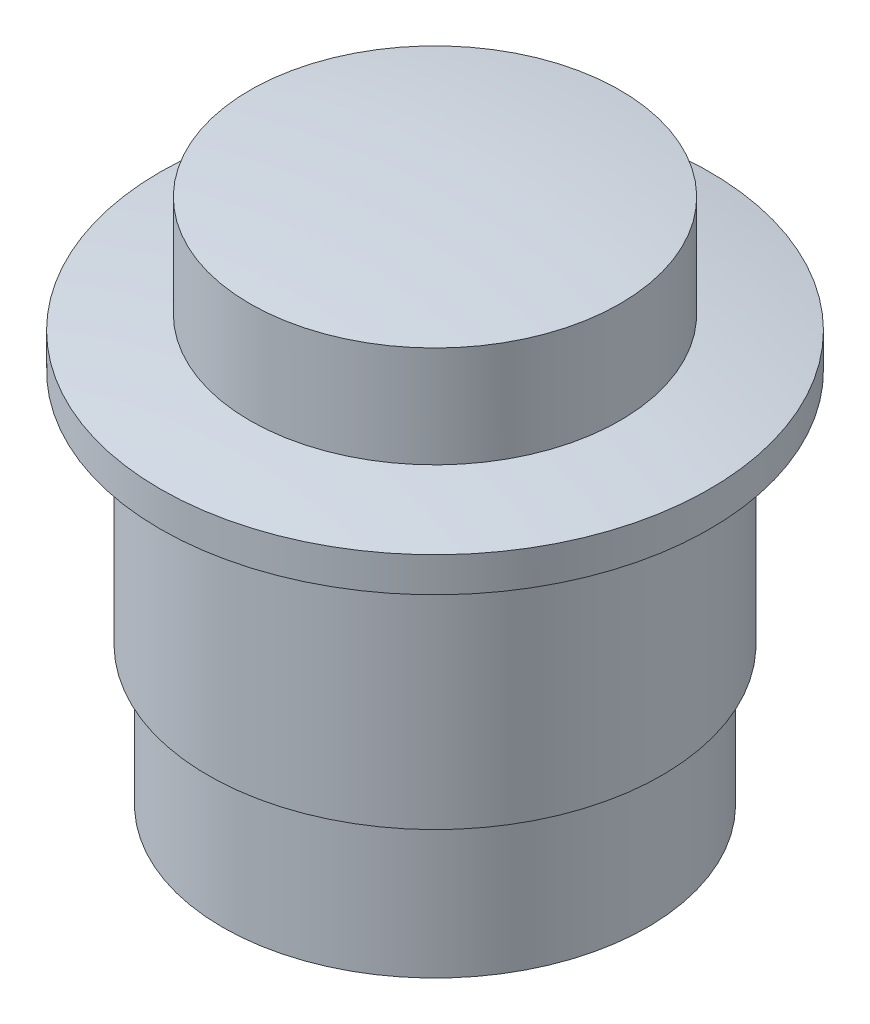
SolidWorks part; units mm, degrees
ref_plane "Front Plane" through (0, 0, 0) normal (0, 0, 1) x (1, 0, 0)
ref_plane "Top Plane" through (0, 0, 0) normal (0, 1, 0) x (1, 0, 0)
ref_plane "Right Plane" through (0, 0, 0) normal (1, 0, 0) x (0, 0, -1)
sketch "Sketch1" plane through (0, 0, 0) normal (0, 1, 0) x (1, 0, 0)
  circle A0 centre (0, 0) radius 7.35
  dimension "D1" = 14.7
extrude "Boss-Extrude1" add sketch "Sketch1" along normal blind 4.8
sketch "Sketch2" plane through (0, 4.8, 0) normal (0, 1, 0) x (1, 0, 0)
  circle A0 centre (0, 0) radius 7.85
  dimension "D1" = 15.7
extrude "Boss-Extrude2" add sketch "Sketch2" along normal offset from surface (8.2 mm away) 13 up to face at (0, 0, 7.35)
sketch "Sketch3" plane through (0, 0, 0) normal (0, 0, 1) x (1, 0, 0)
  line L0 (-7.85, 13) -> (-9.5, 13)
  line L1 (-9.5, 13) -> (-9.5, 14.2)
  line L2 (0, 15.2009) -> (0, -2.1066) construction
  line L3 (-6.4, 14.6995) -> (-6.4, 18.1995)
  line L4 (0, 18.6108) -> (0, 13)
  line L5 (7.85, 13) -> (-7.85, 13) construction
  line L6 (0, 13) -> (-7.85, 13)
  arc A0 (-6.4, 14.6995) -> (-9.5, 14.2) centre (0, -34.8892) ccw
  arc A1 (0, 18.6108) -> (-6.4, 18.1995) centre (0, -31.3892) ccw
  arc A2 (-49.9694, -33.1392) -> (49.9694, -33.1392) centre (0, -31.3892) ccw
  arc A3 (-49.9694, -33.1392) -> (49.9694, -33.1392) centre (0, -34.8892) ccw
  dimension "D3" = 100
  dimension "D1" = 19
  dimension "D2" = 1.2
  dimension "D4" = 12.8
  dimension "D5" = 3.5
revolve "Revolve2" add sketch "Sketch3" angle 360 about L2
